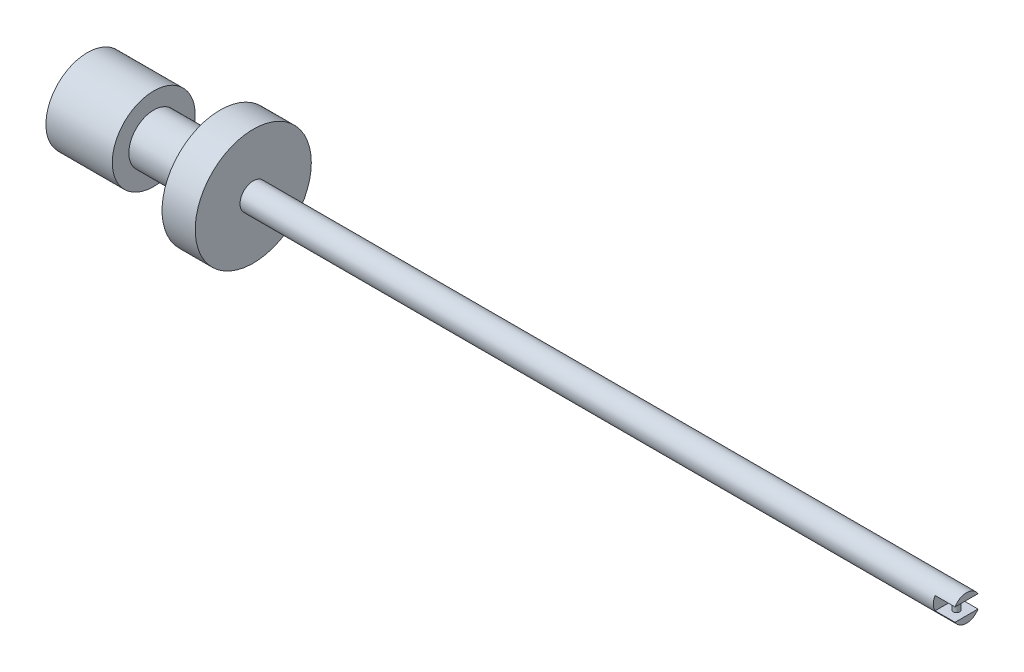
SolidWorks part; units mm, degrees
ref_plane "Front Plane" through (0, 0, 0) normal (0, 0, 1) x (1, 0, 0)
ref_plane "Top Plane" through (0, 0, 0) normal (0, 1, 0) x (1, 0, 0)
ref_plane "Right Plane" through (0, 0, 0) normal (1, 0, 0) x (0, 0, -1)
sketch "Sketch1" plane through (0, 0, 0) normal (1, 0, 0) x (0, 0, -1)
  circle A0 centre (0, 0) radius 12.5
extrude "Boss-Extrude1" add sketch "Sketch1" along normal blind 20 contours A0
sketch "Sketch2" plane through (20, 0, 0) normal (1, 0, 0) x (0, 0, -1)
  circle A0 centre (0, 0) radius 7.5
extrude "Boss-Extrude2" add sketch "Sketch2" along normal blind 20
sketch "Sketch3" plane through (40, 0, 0) normal (1, 0, 0) x (0, 0, -1)
  circle A0 centre (0, 0) radius 17.5
extrude "Boss-Extrude3" add sketch "Sketch3" along normal blind 10
sketch "Sketch4" plane through (50, 0, 0) normal (1, 0, 0) x (0, 0, -1)
  circle A0 centre (0, 0) radius 4
extrude "Boss-Extrude4" add sketch "Sketch4" along normal blind 215 contours A0
sketch "Sketch5" plane through (265, 0, 0) normal (1, 0, 0) x (0, 0, -1)
  line L1 (-6, -2) -> (6, -2)
  line L2 (-6, -2) -> (-6, 2)
  line L3 (-6, 2) -> (6, 2)
  line L4 (6, -2) -> (6, 2)
extrude "Cut-Extrude1" cut sketch "Sketch5" against normal blind 6
sketch "Sketch6" plane through (0, -2, 0) normal (0, 1, 0) x (1, 0, 0)
  circle A0 centre (262, 0) radius 1
extrude "Boss-Extrude5" add sketch "Sketch6" along normal up to surface (4 mm away) up to face at (262, 2, 0)
